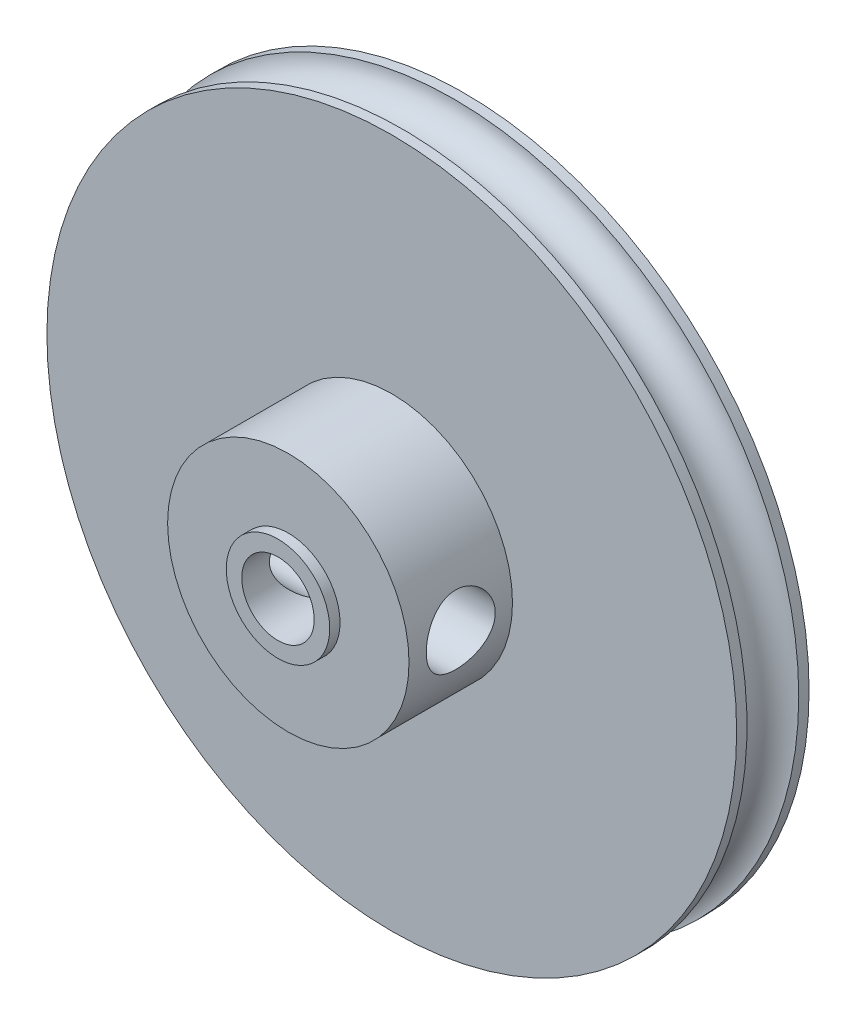
SolidWorks part; units mm, degrees
ref_plane "Plan de face" through (0, 0, 0) normal (0, 0, 1) x (1, 0, 0)
ref_plane "Plan de dessus" through (0, 0, 0) normal (0, 1, 0) x (1, 0, 0)
ref_plane "Plan de droite" through (0, 0, 0) normal (1, 0, 0) x (0, 0, -1)
sketch "Esquisse1" plane through (0, 0, 0) normal (0, 0, 1) x (1, 0, 0)
  circle A0 centre (0, 0) radius 20
  circle A1 centre (0, 0) radius 2.1
  dimension "D1" = 4.2
  dimension "D2" = 40
extrude "Boss.-Extru.1" add sketch "Esquisse1" along normal blind 4.2
sketch "Esquisse2" plane through (0, 0, 4.2) normal (0, 0, 1) x (1, 0, 0)
  circle A0 centre (0, 0) radius 7
  circle A1 centre (0, 0) radius 2.1
  circle A2 centre (0, 0) radius 2.1 construction
  dimension "D1" = 14
extrude "Boss.-Extru.2" add sketch "Esquisse2" along normal blind 6
ref_plane "Plan1" through (0, 0, 0) normal (1, 0, 0) x (0, 0, -1)
sketch "Esquisse3" plane through (0, 0, 0) normal (1, 0, 0) x (0, 0, -1)
  line L0 (0, 20) -> (-4.2, 20) construction
  line L1 (0, 0) -> (-29.2707, 0) construction
  circle A0 centre (-2.1, 20) radius 1.5
  dimension "D1" = 3
revolve "Enlèvement de matière-Révolution1" cut sketch "Esquisse3" angle 360 about L1
sketch "Esquisse5" plane through (0, 0, 0) normal (1, 0, 0) x (0, 0, -1)
  line L0 (-10.2, 7) -> (-10.2, -7) construction
  circle A0 centre (-7.2, 0) radius 2
  dimension "D2" = 4
  dimension "D1" = 3
extrude "Enlèv. mat.-Extru.1" cut sketch "Esquisse5" against normal through all and the other way through all
sketch "Esquisse6" plane through (0, 0, 0) normal (0, 0, -1) x (-1, 0, 0)
  circle A0 centre (0, 0) radius 3
  circle A1 centre (0, 0) radius 2.1
  circle A2 centre (0, 0) radius 2.1 construction
  dimension "D1" = 6
sketch "Esquisse7" plane through (0, 0, 10.2) normal (0, 0, 1) x (1, 0, 0)
  circle A0 centre (0, 0) radius 3
  circle A1 centre (0, 0) radius 2.1
  circle A2 centre (0, 0) radius 2.1 construction
  dimension "D1" = 6
extrude "Boss.-Extru.4" add sketch "Esquisse7" along normal blind 0.6
sketch "Esquisse8" plane through (0, 0, 0) normal (0, 0, -1) x (-1, 0, 0)
  circle A0 centre (0, 0) radius 3
  circle A1 centre (0, 0) radius 2.1
  circle A2 centre (0, 0) radius 2.1 construction
  dimension "D1" = 6
extrude "Boss.-Extru.5" add sketch "Esquisse8" along normal blind 0.5
